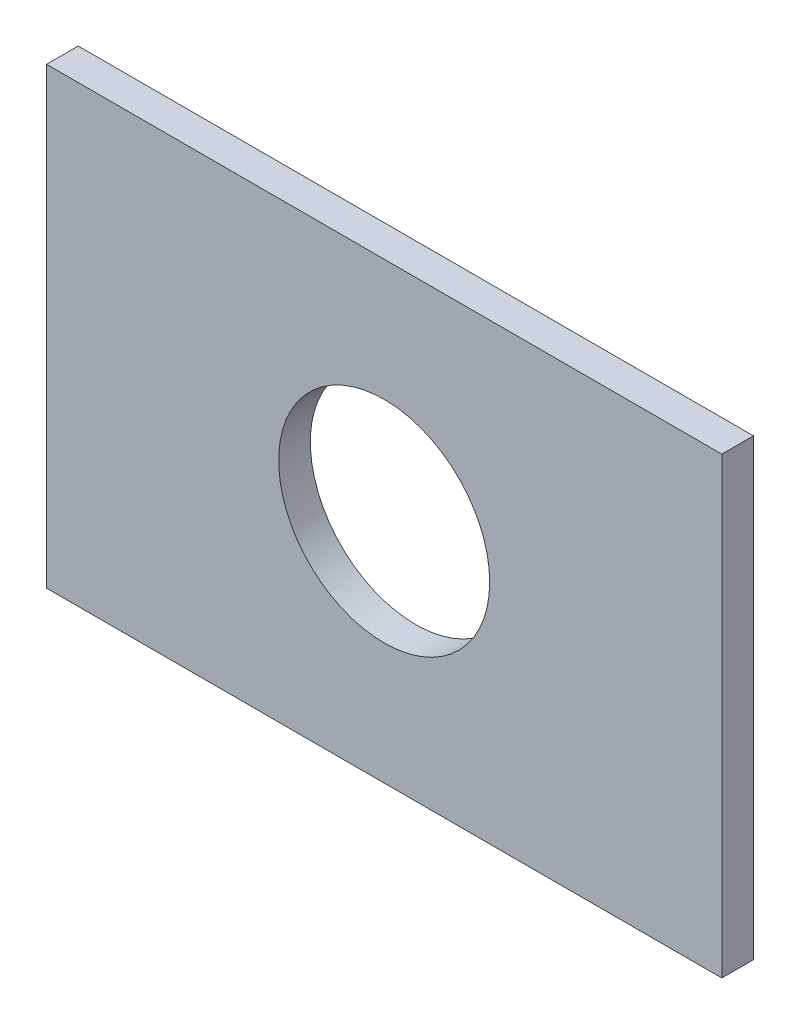
SolidWorks part; units mm, degrees
material "3.3535 (EN-AW 5754)"
ref_plane "Plan de face" through (0, 0, 0) normal (0, 0, 1) x (1, 0, 0)
ref_plane "Plan de dessus" through (0, 0, 0) normal (0, 1, 0) x (1, 0, 0)
ref_plane "Plan de droite" through (0, 0, 0) normal (1, 0, 0) x (0, 0, -1)
sketch "Esquisse1" plane through (0, 0, 0) normal (0, 0, 1) x (1, 0, 0)
  line L1 (-32, -21.5) -> (32, -21.5)
  line L2 (-32, -21.5) -> (-32, 21.5)
  line L3 (-32, 21.5) -> (32, 21.5)
  line L4 (32, -21.5) -> (32, 21.5)
  circle A0 centre (0, 0) radius 10
  dimension "D5" = 20
  dimension "D1" = 32
  dimension "D2" = 32
  dimension "D3" = 21.5
  dimension "D4" = 21.5
extrude "Extrusion1" add sketch "Esquisse1" along normal blind 3
